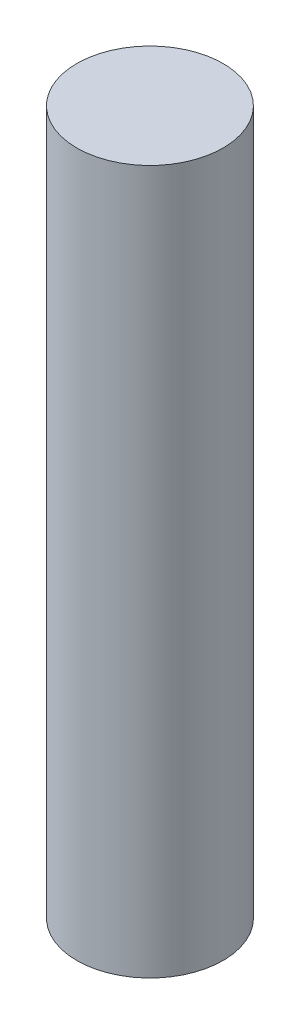
SolidWorks part; units mm, degrees
ref_plane "Front Plane" through (0, 0, 0) normal (0, 0, 1) x (1, 0, 0)
ref_plane "Top Plane" through (0, 0, 0) normal (0, 1, 0) x (1, 0, 0)
ref_plane "Right Plane" through (0, 0, 0) normal (1, 0, 0) x (0, 0, -1)
sketch "Sketch1" plane through (0, 0, 0) normal (0, 1, 0) x (1, 0, 0)
  circle A0 centre (0, 0) radius 2.6
  dimension "D1" = 5.2
extrude "Boss-Extrude1" add sketch "Sketch1" along normal blind 25
